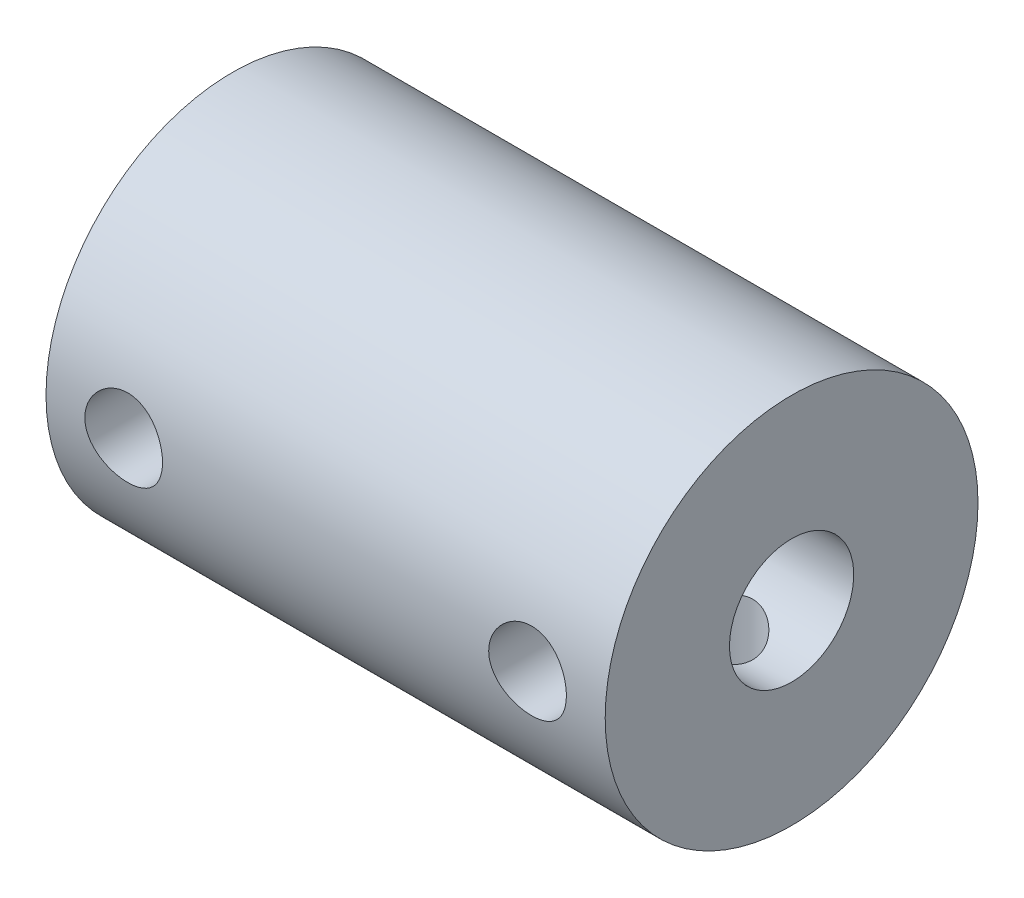
SolidWorks part; units mm, degrees
material "5052-H32"
ref_plane "Front Plane" through (0, 0, 0) normal (0, 0, 1) x (1, 0, 0)
ref_plane "Top Plane" through (0, 0, 0) normal (0, 1, 0) x (1, 0, 0)
ref_plane "Right Plane" through (0, 0, 0) normal (1, 0, 0) x (0, 0, -1)
sketch "Sketch2" plane through (0, 0, 0) normal (0, 0, 1) x (1, 0, 0)
  line L1 (0, 6) -> (18, 6) construction
  line L2 (18, 6) -> (18, 2) construction
  line L3 (18, 2) -> (0, 2) construction
  line L7 (0, 6) -> (18, 6)
  line L8 (18, 6) -> (18, 2)
  line L9 (18, 2) -> (0, 2)
  line L12 (0, 6) -> (0, 2)
  line L15 (0, 0) -> (7, 0) construction
revolve "Revolve1" add sketch "Sketch2" angle 360 about L15
ref_plane "Plane1" through (0, -6, 0) normal (0, -1, 0) x (-1, 0, 0)
hole_wizard "M3 Tapped Hole1" positions "Sketch3" profile "Sketch5" tap size "M3" standard "ISO"
sketch "Sketch3" plane through (0, -6, 0) normal (0, -1, 0) x (-1, 0, 0)
  point P0 (-15.5, 0)
  point P2 (-2.5, 0)
sketch "Sketch5" plane through (15.5, -6, 0) normal (1, 0, 0) x (0, 0, -1)
  line L0 (0, 0) -> (0, 4)
  line L1 (0, 4) -> (1.25, 4)
  line L2 (1.25, 4) -> (1.25, 0)
  line L5 (1.25, 0) -> (0, 0)
  line L11 (0, -6.35) -> (0, 107.95) construction
  dimension "Thru Tap Drill Dia." = 2.5
  dimension "Thru Tap Drill Depth" = 4
cosmetic thread "Hole Thread1" parameters "D2"=3
cosmetic thread "Hole Thread2" parameters "D2"=3
ref_plane "Plane2" through (0, 0, 6) normal (0, 0, 1) x (1, 0, 0)
hole_wizard "M3 Tapped Hole2" positions "Sketch6" profile "Sketch7" tap size "M3" standard "ISO"
sketch "Sketch6" plane through (0, 0, 6) normal (0, 0, 1) x (1, 0, 0)
  point P0 (2.5, 0)
  point P3 (15.5, 0)
sketch "Sketch7" plane through (2.5, 0, 6) normal (1, 0, 0) x (0, -1, 0)
  line L0 (0, 0) -> (0, 4)
  line L1 (0, 4) -> (1.25, 4)
  line L2 (1.25, 4) -> (1.25, 0)
  line L5 (1.25, 0) -> (0, 0)
  line L11 (0, -6.35) -> (0, 107.95) construction
  dimension "Thru Tap Drill Dia." = 2.5
  dimension "Thru Tap Drill Depth" = 4
cosmetic thread "Hole Thread3" parameters "D2"=3
cosmetic thread "Hole Thread4" parameters "D2"=3
